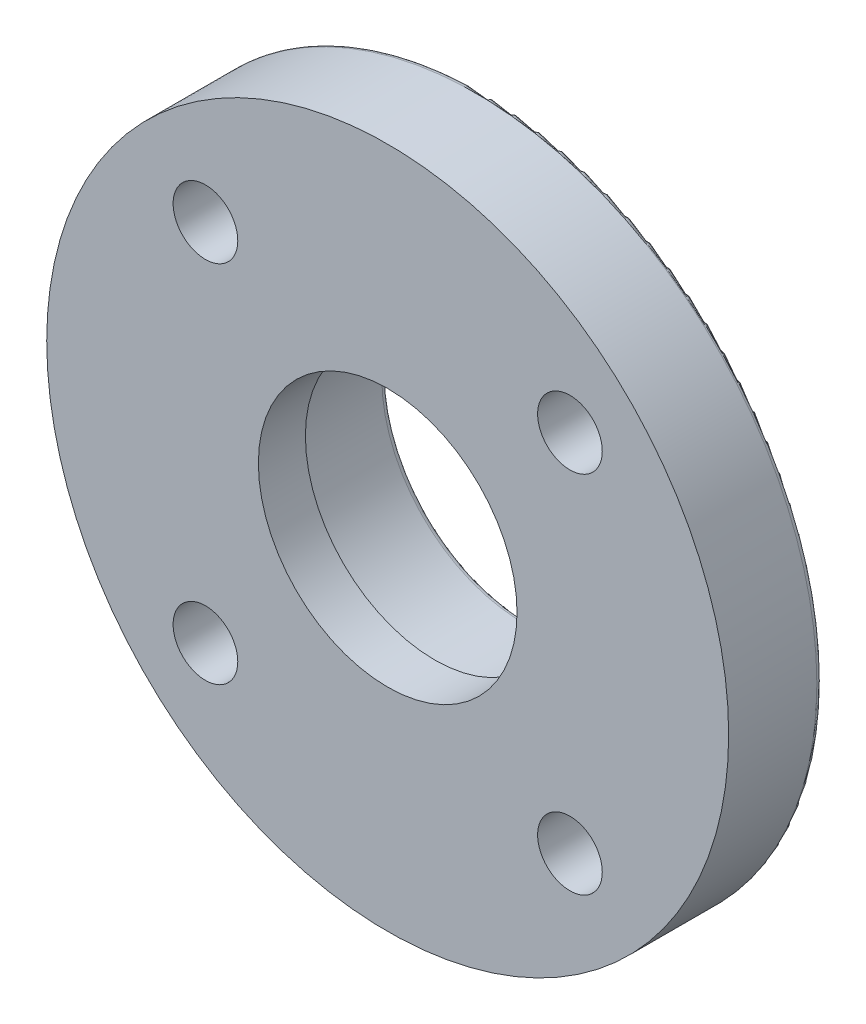
SolidWorks part; units mm, degrees
material "POM Copolímero acetal"
ref_plane "Alzado" through (0, 0, 0) normal (0, 0, 1) x (1, 0, 0)
ref_plane "Planta" through (0, 0, 0) normal (0, 1, 0) x (1, 0, 0)
ref_plane "Vista lateral" through (0, 0, 0) normal (1, 0, 0) x (0, 0, -1)
sketch "Croquis1" plane through (0, 0, 0) normal (0, 0, 1) x (1, 0, 0)
  line L0 (0, 20) -> (0, -20) construction
  line L6 (-15.5, -15.5) -> (15.5, -15.5) construction
  line L7 (-15.5, -15.5) -> (-15.5, 15.5) construction
  line L8 (-15.5, 15.5) -> (15.5, 15.5) construction
  line L9 (15.5, -15.5) -> (15.5, 15.5) construction
  circle A0 centre (-15.5, 15.5) radius 2.75
  circle A1 centre (15.5, 15.5) radius 2.75
  circle A2 centre (15.5, -15.5) radius 2.75
  circle A3 centre (-15.5, -15.5) radius 2.75
  circle A4 centre (0, 0) radius 12
  circle A5 centre (0, 0) radius 29
  dimension "D3" = 24
  dimension "D1" = 58
  dimension "D5" = 5.5
  dimension "D2" = 31
  dimension "D4" = 15.5
  dimension "D6" = 15.5
extrude "Saliente-Extruir1" add sketch "Croquis1" against normal blind 8
sketch "Croquis2" plane through (0, 0, -8) normal (0, 0, -1) x (-1, 0, 0)
  circle A0 centre (0, 0) radius 12
  circle A1 centre (0, 0) radius 16
  dimension "D1" = 32
  dimension "D2" = 24
extrude "Saliente-Extruir2" add sketch "Croquis2" along normal blind 4
ref_plane "Plano1" through (0, 0, -4) normal (0, 0, -1) x (-1, 0, 0)
sketch "Croquis3" plane through (0, 0, -4) normal (0, 0, -1) x (-1, 0, 0)
  circle A0 centre (0, 0) radius 11
  circle A1 centre (0, 0) radius 12
  dimension "D1" = 22
  dimension "D2" = 24
extrude "Saliente-Extruir3" add sketch "Croquis3" against normal blind 4
fillet "Redondeo2" radius 0.5 3 edges at (-12, 0, -12) (-16, 0, -12) (29, 0, -8)
